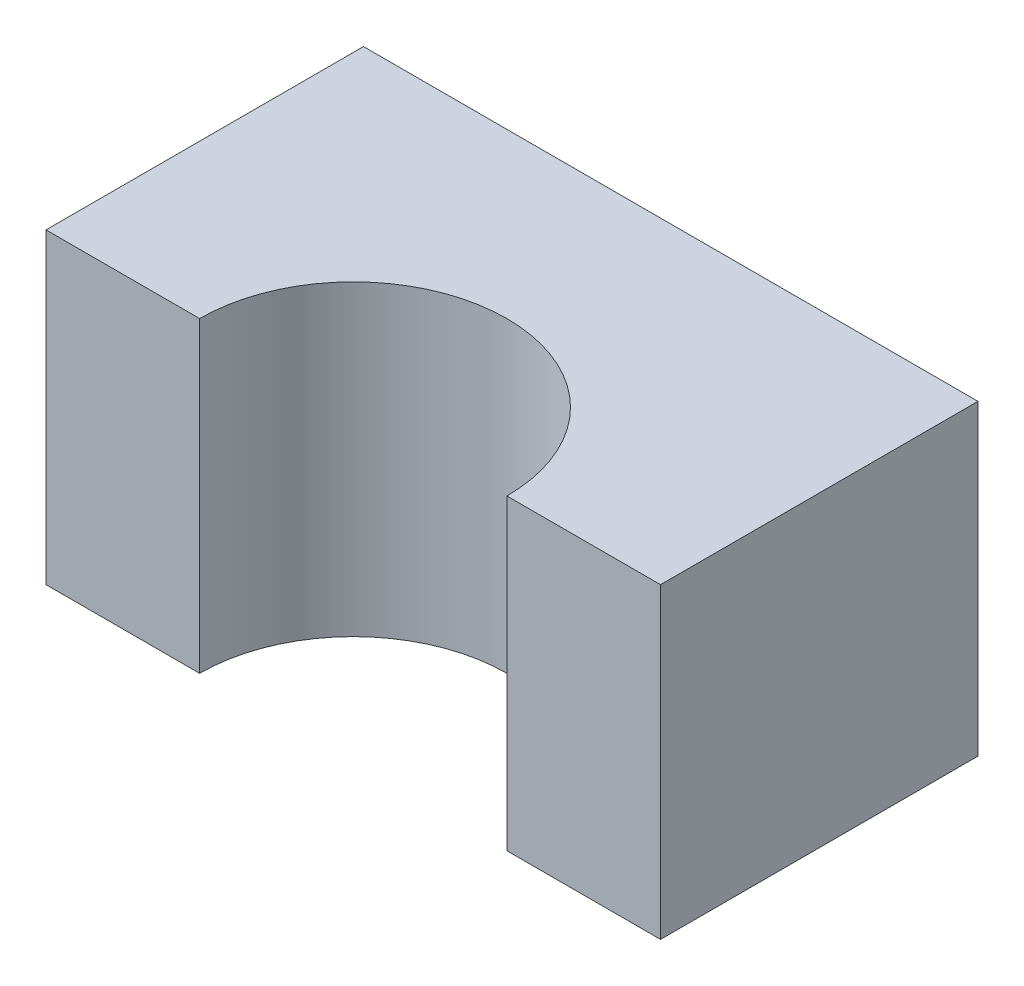
SolidWorks part; units mm, degrees
ref_plane "Front Plane" through (0, 0, 0) normal (0, 0, 1) x (1, 0, 0)
ref_plane "Top Plane" through (0, 0, 0) normal (0, 1, 0) x (1, 0, 0)
ref_plane "Right Plane" through (0, 0, 0) normal (1, 0, 0) x (0, 0, -1)
sketch "Sketch1" plane through (0, 0, 0) normal (0, 0, 1) x (1, 0, 0)
  line L0 (-31.1077, 122.487) -> (-31.1077, -78.514) construction
  line L1 (-25.1077, 24.016) -> (-19.1077, 24.016)
  line L2 (-25.1077, 24.016) -> (-25.1077, 21.016)
  line L3 (-25.1077, 21.016) -> (-19.1077, 21.016)
  line L4 (-19.1077, 24.016) -> (-19.1077, 21.016)
  dimension "D1" = 3
  dimension "D2" = 6
  dimension "D3" = 6
  dimension "D4" = 6
extrude "Boss-Extrude1" add sketch "Sketch1" along normal blind 3.1
sketch "Sketch2" plane through (0, 24.016, 0) normal (0, 1, 0) x (1, 0, 0)
  line L0 (-19.1077, -3.1) -> (-25.1077, -3.1) construction
  circle A0 centre (-22.1077, -3.1) radius 1.5
extrude "Cut-Extrude1" cut sketch "Sketch2" against normal blind 9
